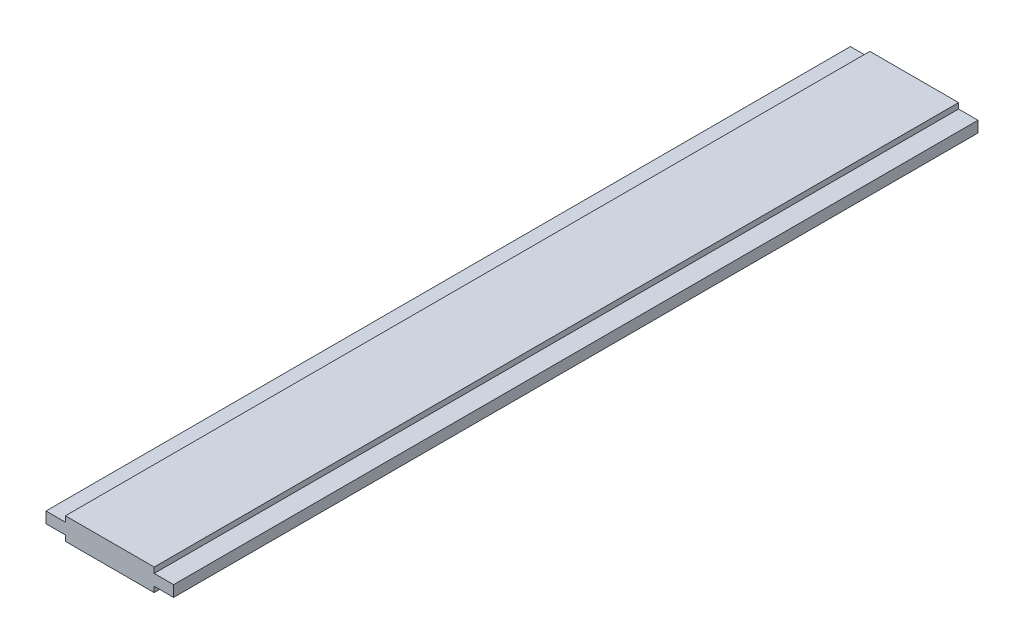
SolidWorks part; units mm, degrees
ref_plane "Front Plane" through (0, 0, 0) normal (0, 0, 1) x (1, 0, 0)
ref_plane "Top Plane" through (0, 0, 0) normal (0, 1, 0) x (1, 0, 0)
ref_plane "Right Plane" through (0, 0, 0) normal (1, 0, 0) x (0, 0, -1)
sketch "Sketch1" plane through (0, 0, 0) normal (0, 0, 1) x (1, 0, 0)
  line L0 (0, 0) -> (0, 18) construction
  line L1 (-4, 17.5) -> (-4, 17)
  line L2 (-4, 19) -> (4, 19)
  line L3 (-4, 19) -> (-4, 18.5)
  line L4 (-4, 17) -> (4, 17)
  line L5 (4, 19) -> (4, 18.5)
  line L6 (-4, 19) -> (4, 17) construction
  line L7 (-4, 17) -> (4, 19) construction
  line L8 (-5.75, 18.5) -> (-4, 18.5)
  line L9 (-5.75, 18.5) -> (-5.75, 17.5)
  line L10 (-5.75, 17.5) -> (-4, 17.5)
  line L11 (5.75, 18.5) -> (5.75, 17.5)
  line L12 (-5.75, 18.5) -> (5.75, 17.5) construction
  line L13 (-5.75, 17.5) -> (5.75, 18.5) construction
  line L14 (4, 18.5) -> (5.75, 18.5)
  line L15 (4, 17.5) -> (5.75, 17.5)
  line L17 (4, 17.5) -> (4, 17)
  dimension "D1" = 18
  dimension "D2" = 8
  dimension "D3" = 2
  dimension "D4" = 11.5
  dimension "D5" = 1
  dimension "D6" = 8
extrude "Boss-Extrude1" add sketch "Sketch1" along normal blind 72.5 contours L4 L17 L15 L11 L14 L5 L2 L3 L8 L9 L10 L1
